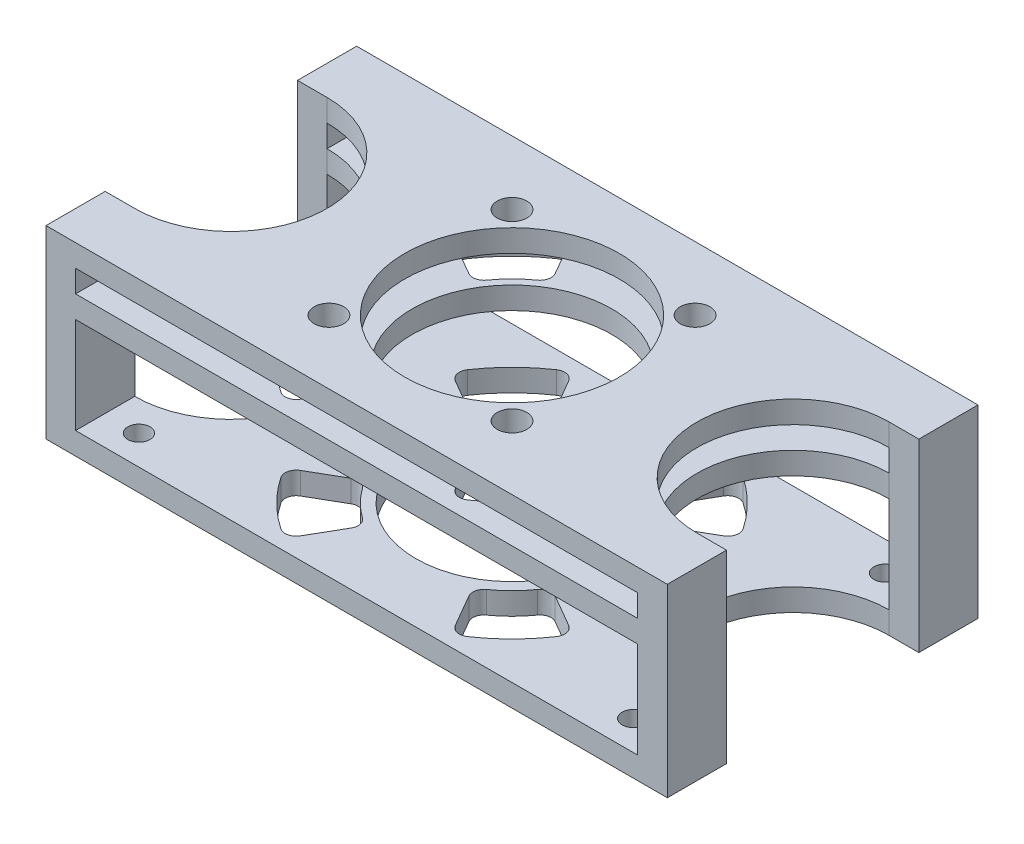
SolidWorks part; units mm, degrees
material "6061 合金"
ref_plane "前视基准面" through (0, 0, 0) normal (0, 0, 1) x (1, 0, 0)
ref_plane "上视基准面" through (0, 0, 0) normal (0, 1, 0) x (1, 0, 0)
ref_plane "右视基准面" through (0, 0, 0) normal (1, 0, 0) x (0, 0, -1)
sketch "草图1" plane through (0, 0, 0) normal (0, 1, 0) x (1, 0, 0)
  line L1 (-42, -21) -> (42, -21)
  line L2 (-42, -21) -> (-42, 21)
  line L3 (-42, 21) -> (42, 21)
  line L4 (42, -21) -> (42, 21)
  line L5 (-42, -21) -> (42, 21) construction
  line L6 (-42, 21) -> (42, -21) construction
  point P0 (0, 0)
  dimension "D1" = 84
  dimension "D2" = 42
extrude "凸台-拉伸1" add sketch "草图1" along normal blind 3
sketch "草图2" plane through (0, 3, 0) normal (0, 1, 0) x (1, 0, 0)
  line L0 (-42, -21) -> (42, -21) construction
  line L1 (-42, 21) -> (-38, 21)
  line L2 (-42, 21) -> (-42, -21)
  line L3 (-42, -21) -> (-38, -21)
  line L4 (-38, 21) -> (-38, -21)
  line L6 (42, 21) -> (38, 21)
  line L7 (42, 21) -> (42, -21)
  line L8 (42, -21) -> (38, -21)
  line L9 (38, 21) -> (38, -21)
  dimension "D1" = 4
  dimension "D2" = 4
extrude "凸台-拉伸2" add sketch "草图2" along normal blind 19
sketch "草图3" plane through (0, 22, 0) normal (0, 1, 0) x (1, 0, 0)
  line L1 (-42, 21) -> (42, 21)
  line L2 (-42, 21) -> (-42, -21)
  line L3 (-42, -21) -> (42, -21)
  line L4 (42, 21) -> (42, -21)
extrude "凸台-拉伸3" add sketch "草图3" along normal blind 3
sketch "草图5" plane through (0, 0, 21) normal (0, 0, 1) x (1, 0, 0)
  line L0 (-38, 22) -> (-38, 3) construction
  line L1 (-38, 19) -> (38, 19)
  line L2 (-38, 19) -> (-38, 16)
  line L3 (-38, 16) -> (38, 16)
  line L4 (38, 19) -> (38, 16)
  line L5 (38, 22) -> (38, 3) construction
  line L6 (-38, 22) -> (38, 22) construction
  dimension "D1" = 3
  dimension "D2" = 3
extrude "凸台-拉伸4" add sketch "草图5" against normal blind 42
sketch "草图4" plane through (0, 25, 0) normal (0, 1, 0) x (1, 0, 0)
  line L0 (0, 0) -> (0, 17.5) construction
  line L1 (0, 0) -> (12.3744, 12.3744) construction
  circle A0 centre (0, 0) radius 14.5
  circle A1 centre (0, 0) radius 17.5 construction
  circle A3 centre (12.3744, 12.3744) radius 2
  circle A4 centre (12.3744, -12.3744) radius 2
  circle A5 centre (-12.3744, -12.3744) radius 2
  circle A6 centre (-12.3744, 12.3744) radius 2
  point P16 (0, 0)
  dimension "D1" = 29
  dimension "D2" = 35
  dimension "D4" = 4
  dimension "D3" = 45
  dimension "D5" = 4
extrude "切除-拉伸1" cut sketch "草图4" against normal up to next
sketch "草图6" plane through (0, 19, 0) normal (0, 1, 0) x (1, 0, 0)
  circle A0 centre (0, 0) radius 13.5
  dimension "D1" = 27
extrude "切除-拉伸2" cut sketch "草图6" against normal blind 3
sketch "草图7" plane through (0, 0, 0) normal (0, -1, 0) x (1, 0, 0)
  circle A0 centre (0, 0) radius 13
  dimension "D1" = 26
extrude "切除-拉伸3" cut sketch "草图7" against normal blind 3
sketch "草图8" plane through (0, 25, 0) normal (0, 1, 0) x (1, 0, 0)
  line L1 (0, 21) -> (0, -21) construction
  line L2 (42, 21) -> (-42, 21) construction
  line L3 (-42, -21) -> (42, -21) construction
  line L9 (42, -21) -> (42, 21) construction
  line L10 (42, 0) -> (-42, 0) construction
  line L11 (-42, 21) -> (-42, -21) construction
  line L12 (42, -13) -> (38, -13)
  line L13 (-42, 13) -> (-38, 13)
  line L14 (-42, 13) -> (-42, -13)
  line L15 (-42, -13) -> (-38, -13)
  line L16 (-38, 13) -> (-38, -13) construction
  line L17 (42, 13) -> (42, -13)
  line L18 (42, 13) -> (38, 13)
  arc A2 (-38, -13) -> (-38, 13) centre (-38, 0) ccw
  arc A3 (38, -13) -> (38, 13) centre (38, 0) cw
  dimension "D1" = 4
  dimension "D2" = 26
extrude "切除-拉伸4" cut sketch "草图8" against normal through all
sketch "草图9" plane through (0, 0, 0) normal (0, -1, 0) x (1, 0, 0)
  line L0 (0, 0) -> (0, 37.5) construction
  line L1 (0, 0) -> (33.4127, 17.0246) construction
  line L2 (-37.5, 0) -> (37.5, 0) construction
  circle A0 centre (0, 0) radius 37.5 construction
  circle A1 centre (33.4127, 17.0246) radius 1.5
  circle A2 centre (-33.4127, 17.0246) radius 1.5
  circle A3 centre (33.4127, -17.0246) radius 1.5
  circle A4 centre (-33.4127, -17.0246) radius 1.5
  dimension "D1" = 75
  dimension "D3" = 3
  dimension "D2" = 63
extrude "切除-拉伸5" cut sketch "草图9" against normal blind 3
sketch "草图10" plane through (0, 0, 0) normal (0, -1, 0) x (1, 0, 0)
  line L0 (0, 0) -> (0, 22.5) construction
  line L1 (7.25, 12.5574) -> (11.25, 19.4856)
  line L2 (12.5574, 7.25) -> (19.4856, 11.25)
  line L3 (12.5574, -7.25) -> (19.4856, -11.25)
  line L4 (7.25, -12.5574) -> (11.25, -19.4856)
  line L5 (-7.25, -12.5574) -> (-11.25, -19.4856)
  line L6 (-12.5574, -7.25) -> (-19.4856, -11.25)
  line L7 (-12.5574, 7.25) -> (-19.4856, 11.25)
  line L8 (-7.25, 12.5574) -> (-11.25, 19.4856)
  circle A0 centre (-12.3744, 12.3744) radius 3.75 construction
  circle A1 centre (12.3744, 12.3744) radius 3.75 construction
  circle A2 centre (12.3744, -12.3744) radius 3.75 construction
  circle A3 centre (-12.3744, -12.3744) radius 3.75 construction
  arc A4 (-12.5574, -7.25) -> (-7.25, -12.5574) centre (0, 0) ccw
  arc A5 (-19.4856, -11.25) -> (-11.25, -19.4856) centre (0, 0) ccw
  arc A6 (-7.25, 12.5574) -> (-12.5574, 7.25) centre (0, 0) ccw
  arc A7 (-11.25, 19.4856) -> (-19.4856, 11.25) centre (0, 0) ccw
  arc A8 (7.25, -12.5574) -> (12.5574, -7.25) centre (0, 0) ccw
  arc A9 (11.25, -19.4856) -> (19.4856, -11.25) centre (0, 0) ccw
  arc A10 (19.4856, 11.25) -> (11.25, 19.4856) centre (0, 0) ccw
  arc A11 (12.5574, 7.25) -> (7.25, 12.5574) centre (0, 0) ccw
  point P12 (0, 0)
  point P34 (0, 0)
  dimension "D1" = 7.5
  dimension "D3" = 29
  dimension "D4" = 45
  dimension "D5" = 30
  dimension "D6" = 30
  dimension "D2" = 4
  dimension "D7" = 4
extrude "切除-拉伸6" cut sketch "草图10" against normal up to surface (19 mm away)
fillet "圆角1" radius 1.5 32 edges at (11.25, 1.5, 19.4856) (11.25, 17.5, 19.4856) (19.4856, 1.5, 11.25) (19.4856, 17.5, 11.25) (12.5574, 17.5, 7.25) (12.5574, 1.5, 7.25) (7.25, 17.5, 12.5574) (7.25, 1.5, 12.5574) (-19.4856, 17.5, 11.25) (-11.25, 17.5, 19.4856) (-11.25, 1.5, 19.4856) (-19.4856, 1.5, 11.25) (-7.25, 17.5, 12.5574) (-12.5574, 17.5, 7.25) (-7.25, 1.5, 12.5574) (-12.5574, 1.5, 7.25) (-12.5574, 17.5, -7.25) (-7.25, 17.5, -12.5574) (-11.25, 17.5, -19.4856) (-19.4856, 17.5, -11.25) (-12.5574, 1.5, -7.25) (-19.4856, 1.5, -11.25) (-7.25, 1.5, -12.5574) (-11.25, 1.5, -19.4856) (19.4856, 1.5, -11.25) (12.5574, 1.5, -7.25) (7.25, 1.5, -12.5574) (11.25, 1.5, -19.4856) (11.25, 17.5, -19.4856) (19.4856, 17.5, -11.25) (7.25, 17.5, -12.5574) (12.5574, 17.5, -7.25)
